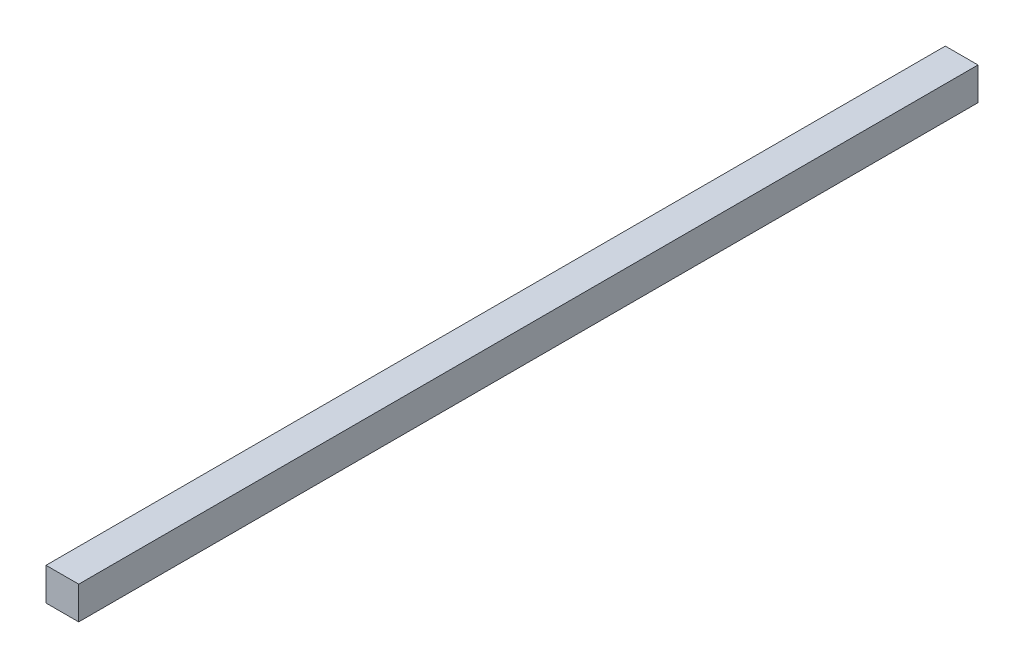
SolidWorks part; units mm, degrees
ref_plane "Front Plane" through (0, 0, 0) normal (0, 0, 1) x (1, 0, 0)
ref_plane "Top Plane" through (0, 0, 0) normal (0, 1, 0) x (1, 0, 0)
ref_plane "Right Plane" through (0, 0, 0) normal (1, 0, 0) x (0, 0, -1)
sketch "Sketch1" plane through (0, 0, 0) normal (0, 0, 1) x (1, 0, 0)
  line L1 (-10, -10) -> (10, -10)
  line L2 (-10, -10) -> (-10, 10)
  line L3 (-10, 10) -> (10, 10)
  line L4 (10, -10) -> (10, 10)
  line L5 (-10, -10) -> (10, 10) construction
  line L6 (-10, 10) -> (10, -10) construction
  point P0 (0, 0)
  dimension "D1" = 20
extrude "Boss-Extrude1" add sketch "Sketch1" along normal blind 550
